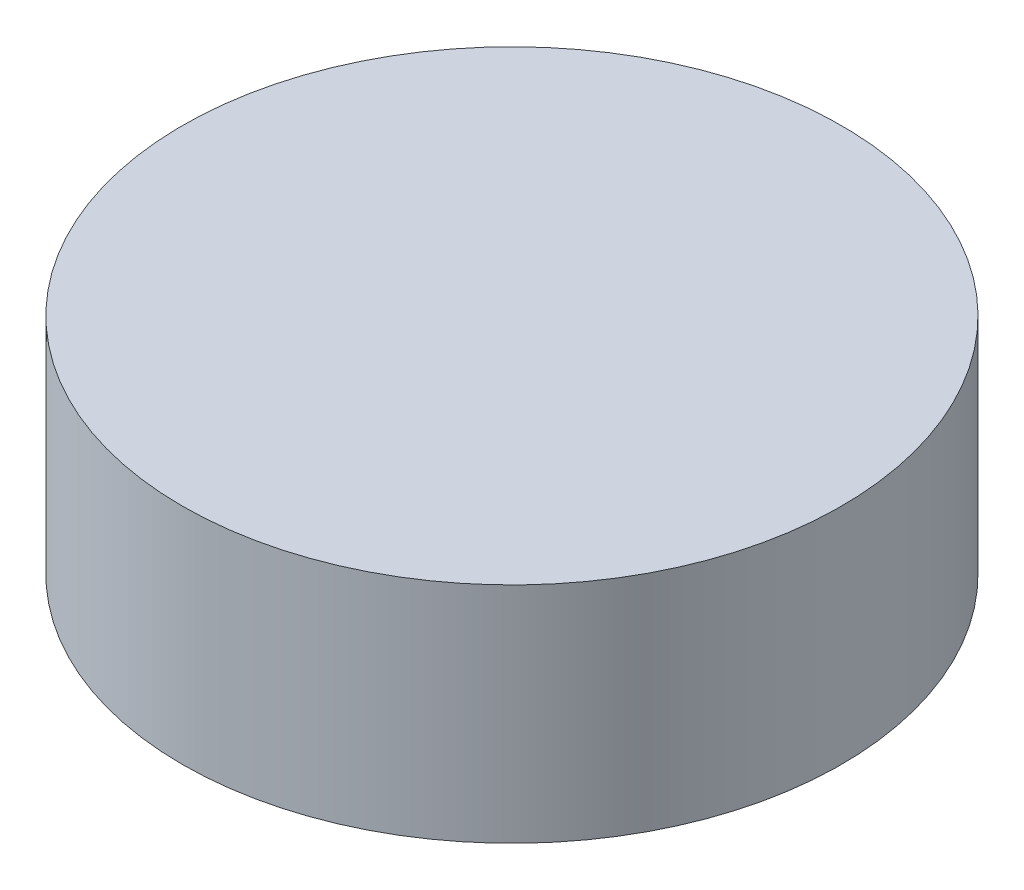
SolidWorks part; units mm, degrees
ref_plane "Front Plane" through (0, 0, 0) normal (0, 0, 1) x (1, 0, 0)
ref_plane "Top Plane" through (0, 0, 0) normal (0, 1, 0) x (1, 0, 0)
ref_plane "Right Plane" through (0, 0, 0) normal (1, 0, 0) x (0, 0, -1)
sketch "Sketch1" plane through (0, 0, 0) normal (0, 1, 0) x (1, 0, 0)
  circle A0 centre (0, 0) radius 44.1844
extrude "Boss-Extrude1" add sketch "Sketch1" along normal blind 30
